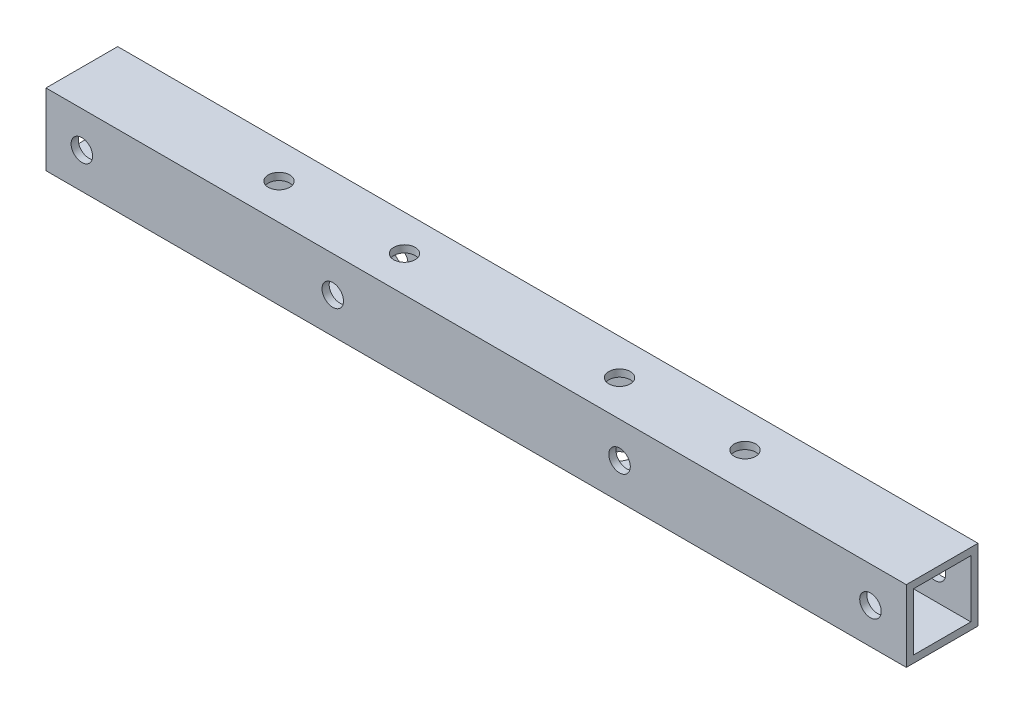
SolidWorks part; units mm, degrees
material "1060 合金"
ref_plane "正面" through (0, 0, 0) normal (0, 0, 1) x (1, 0, 0)
ref_plane "平面" through (0, 0, 0) normal (0, 1, 0) x (1, 0, 0)
ref_plane "右側面" through (0, 0, 0) normal (1, 0, 0) x (0, 0, -1)
sketch "ｽｹｯﾁ1" plane through (0, 0, 0) normal (1, 0, 0) x (0, 0, -1)
  line L1 (-5, -5) -> (5, -5)
  line L2 (-5, -5) -> (-5, 5)
  line L3 (-5, 5) -> (5, 5)
  line L4 (5, -5) -> (5, 5)
  line L5 (-5, -5) -> (5, 5) construction
  line L6 (-5, 5) -> (5, -5) construction
  point P0 (0, 0)
  dimension "D1" = 10
extrude "押し出し-薄板1" add sketch "ｽｹｯﾁ1" along normal blind 120 thin thin type one direction reverse wall 1
sketch "ｽｹｯﾁ2" plane through (0, 0, 5) normal (0, 0, 1) x (1, 0, 0)
  line L0 (0, 0) -> (120, 0) construction
  line L1 (120, 5) -> (120, -5) construction
  line L2 (60, 5) -> (60, -5) construction
  line L3 (120, 5) -> (0, 5) construction
  line L4 (120, -5) -> (0, -5) construction
  line L5 (0, 5) -> (0, -5) construction
  circle A0 centre (5, 0) radius 1.5
  circle A1 centre (115, 0) radius 1.5
  circle A2 centre (40, 0) radius 1.5
  circle A3 centre (80, 0) radius 1.5
  dimension "D1" = 5
  dimension "D2" = 3
  dimension "D3" = 40
extrude "ｶｯﾄ - 押し出し1" cut sketch "ｽｹｯﾁ2" against normal through all
sketch "ｽｹｯﾁ3" plane through (0, 5, 0) normal (0, 1, 0) x (1, 0, 0)
  line L0 (0, 0) -> (50000, 0) construction
  line L2 (60, 5) -> (60, -5) construction
  line L3 (120, 5) -> (0, 5) construction
  line L4 (120, -5) -> (0, -5) construction
  circle A0 centre (45, 0) radius 1.5
  circle A1 centre (75, 0) radius 1.5
  circle A7 centre (27.5, 0) radius 1.5
  circle A8 centre (92.5, 0) radius 1.5
  dimension "D1" = 30
  dimension "D2" = 3
  dimension "D3" = 17.5
extrude "ｶｯﾄ - 押し出し2" cut sketch "ｽｹｯﾁ3" against normal through all
